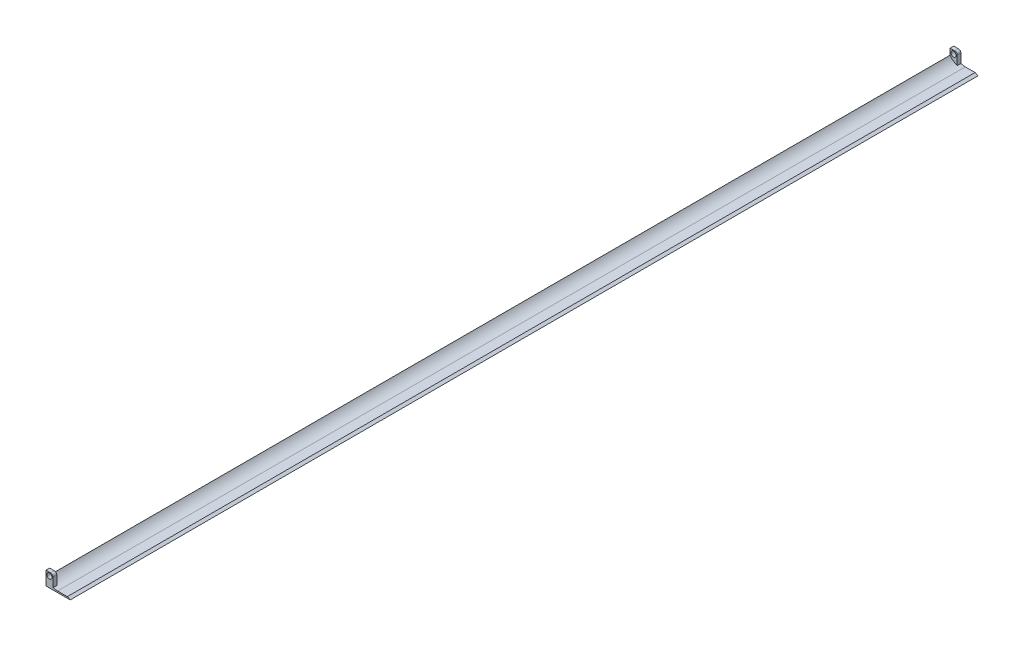
SolidWorks part; units mm, degrees
ref_plane "Front Plane" through (0, 0, 0) normal (0, 0, 1) x (1, 0, 0)
ref_plane "Top Plane" through (0, 0, 0) normal (0, 1, 0) x (1, 0, 0)
ref_plane "Right Plane" through (0, 0, 0) normal (1, 0, 0) x (0, 0, -1)
sketch "Sketch1" plane through (0, 0, 0) normal (0, 0, 1) x (1, 0, 0)
  line L2 (-7.3602, 3.9339) -> (-7.3602, -3.9702)
  line L3 (-7.3602, -3.9702) -> (7.3602, -3.9702)
  line L5 (4.5846, -2.4842) -> (14.7342, -2.4842)
  line L7 (17.7073, -3.9702) -> (7.3602, -3.9702)
  line L8 (14.7342, -2.4842) -> (17.7073, -3.9702)
  arc A0 (-7.3602, 3.9339) -> (4.5846, -2.4842) centre (4.5846, 11.8403) ccw
  point P0 (0, 0)
extrude "Boss-Extrude1" add sketch "Sketch1" along normal blind 939.8
sketch "Sketch2" plane through (0, 0, 939.8) normal (0, 0, 1) x (1, 0, 0)
  line L1 (-7.3602, -3.9702) -> (0, -3.9702)
  line L2 (-7.3602, -3.9702) -> (-7.3602, 10.1801)
  line L3 (-7.3602, 10.1801) -> (-2.54, 10.1801)
  line L4 (0, -3.9702) -> (0, 7.6401)
  circle A0 centre (-3.81, 6.7412) radius 2.667
  arc A2 (0, 7.6401) -> (-2.54, 10.1801) centre (-2.54, 7.6401) ccw
  point P1 (2.0262, 10.1801)
  dimension "D1" = 5.334
  dimension "D2" = 2.54
extrude "Boss-Extrude2" add sketch "Sketch2" against normal blind 3.81
sketch "Sketch3" plane through (0, 0, 0) normal (0, 0, -1) x (-1, 0, 0)
  line L0 (0, -1.7307) -> (0, -3.9702)
  line L1 (7.3602, -3.9702) -> (-17.7073, -3.9702) construction
  line L2 (0, -3.9702) -> (7.3602, -3.9702)
  line L3 (7.3602, 3.9339) -> (7.3602, 10.1801)
  line L7 (7.3602, -3.9702) -> (7.3602, 3.9339)
  line L12 (7.3602, 10.1801) -> (2.54, 10.1801)
  line L13 (0, 7.6401) -> (0, -1.7307)
  line L14 (7.3602, 3.9339) -> (7.3602, 10.1801)
  line L15 (7.3602, 10.1801) -> (2.54, 10.1801)
  line L16 (0, 7.6401) -> (0, -1.7307)
  circle A0 centre (3.81, 6.7412) radius 2.667 construction
  circle A3 centre (3.81, 6.7412) radius 2.667
  arc A4 (0, -1.7307) -> (7.3602, 3.9339) centre (-4.5846, 11.8403) ccw
  arc A5 (2.54, 10.1801) -> (0, 7.6401) centre (2.54, 7.6401) ccw
  arc A10 (2.54, 10.1801) -> (0, 7.6401) centre (2.54, 7.6401) ccw
  dimension "D2" = 0
extrude "Boss-Extrude3" add sketch "Sketch3" against normal blind 3.81
